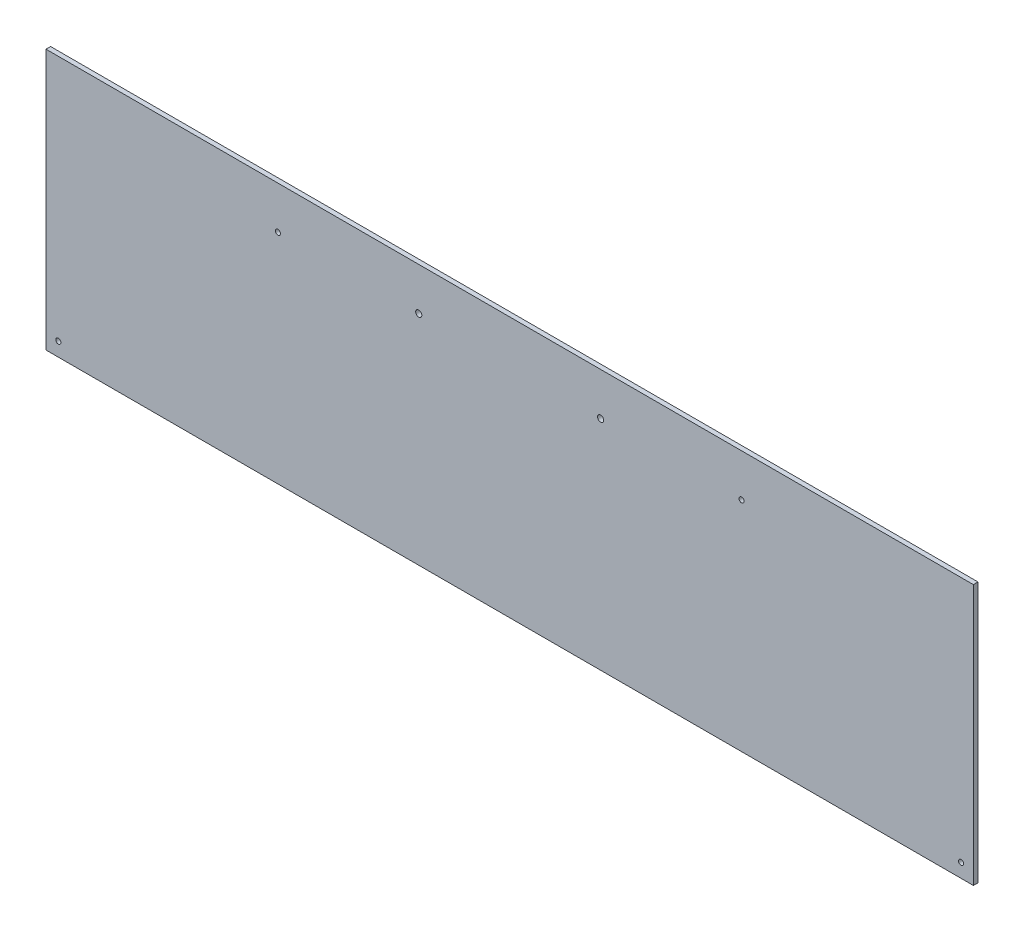
SolidWorks part; units mm, degrees
ref_plane "Front Plane" through (0, 0, 0) normal (0, 0, 1) x (1, 0, 0)
ref_plane "Top Plane" through (0, 0, 0) normal (0, 1, 0) x (1, 0, 0)
ref_plane "Right Plane" through (0, 0, 0) normal (1, 0, 0) x (0, 0, -1)
sketch "Sketch1" plane through (0, 0, 0) normal (0, 0, 1) x (1, 0, 0)
  line L2 (-452, 118.5) -> (-452, -135.5)
  line L4 (452, 118.5) -> (452, -135.5)
  line L10 (-452, -135.5) -> (452, -135.5)
  line L11 (0, -135.5) -> (0, 123.5) construction
  line L16 (-452, -8.5) -> (452, -8.5) construction
  line L25 (-452, 118.5) -> (-228.5, 118.5)
  line L26 (-223.5, 118.5) -> (-2.5, 118.5)
  line L27 (228.5, 118.5) -> (452, 118.5)
  line L28 (2.5, 118.5) -> (223.5, 118.5)
  line L29 (223.5, 118.5) -> (228.5, 118.5)
  line L30 (2.5, 118.5) -> (-2.5, 118.5)
  line L31 (-228.5, 118.5) -> (-223.5, 118.5)
  circle A27 centre (440, -122) radius 2.5
  circle A28 centre (-440, -122) radius 2.5
  circle A29 centre (-226, 77) radius 2.5
  circle A30 centre (226, 77) radius 2.5
  circle A31 centre (-88.6172, 77) radius 3
  circle A32 centre (88.6172, 77) radius 3
  point P18 (-452, 118.5)
  dimension "D5" = 12
  dimension "D3" = 12
  dimension "D7" = 41.5
  dimension "D10" = 13.5
  dimension "D6" = 226
  dimension "D8" = 41.5
  dimension "D1" = 254
  dimension "D2" = 904
  dimension "D4" = 452
  dimension "D9" = 13.5
extrude "Boss-Extrude1" add sketch "Sketch1" along normal blind 4.5
